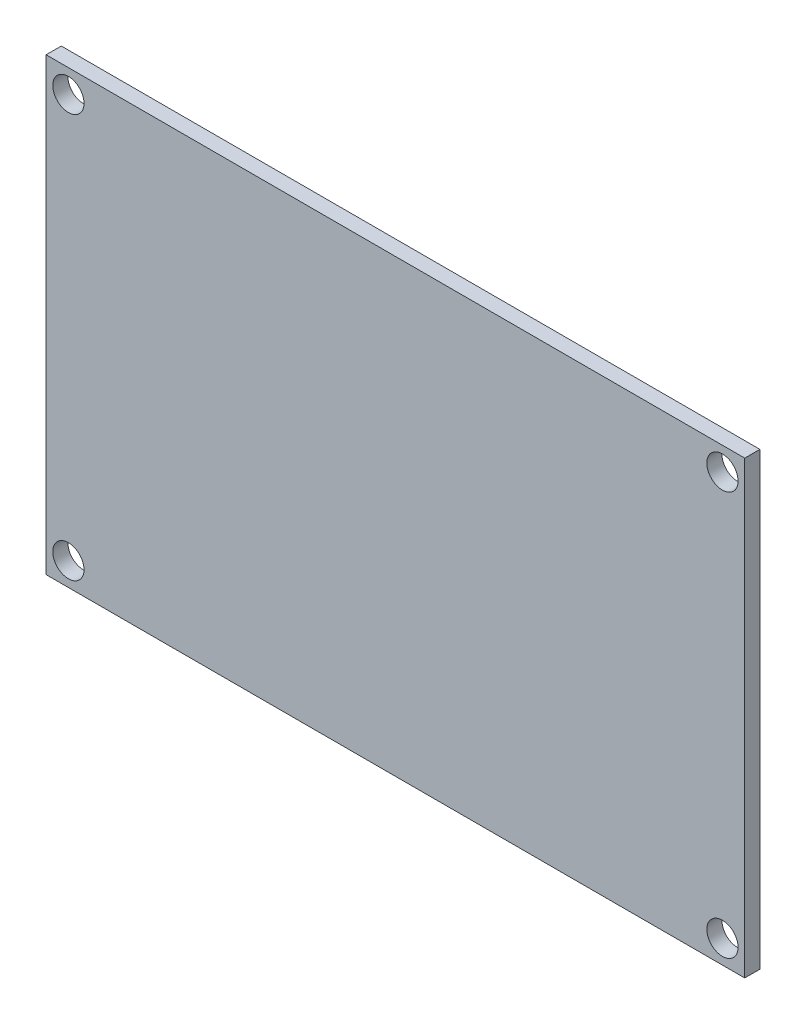
SolidWorks part; units mm, degrees
ref_plane "Front Plane" through (0, 0, 0) normal (0, 0, 1) x (1, 0, 0)
ref_plane "Top Plane" through (0, 0, 0) normal (0, 1, 0) x (1, 0, 0)
ref_plane "Right Plane" through (0, 0, 0) normal (1, 0, 0) x (0, 0, -1)
sketch "Sketch1" plane through (0, 0, 0) normal (0, 0, 1) x (1, 0, 0)
  line L0 (2.35, 45.05) -> (71.35, 45.05) construction
  line L1 (0, 0) -> (73.7, 0)
  line L2 (0, 0) -> (0, 47.5)
  line L3 (0, 47.5) -> (73.7, 47.5)
  line L4 (73.7, 0) -> (73.7, 47.5)
  line L5 (71.35, 45.05) -> (71.35, 2.45) construction
  line L6 (71.35, 2.45) -> (2.35, 2.45) construction
  line L7 (2.35, 2.45) -> (2.35, 45.05) construction
  line L8 (36.85, 47.5) -> (36.85, 45.05) construction
  line L9 (71.35, 23.75) -> (73.7, 23.75) construction
  circle A0 centre (2.35, 45.05) radius 1.65
  circle A1 centre (71.35, 45.05) radius 1.65
  circle A2 centre (2.35, 2.45) radius 1.65
  circle A3 centre (71.35, 2.45) radius 1.65
  dimension "D3" = 3.3
  dimension "D1" = 47.5
  dimension "D2" = 73.7
  dimension "D4" = 69
  dimension "D5" = 42.6
extrude "Boss-Extrude1" add sketch "Sketch1" along normal blind 1.6
